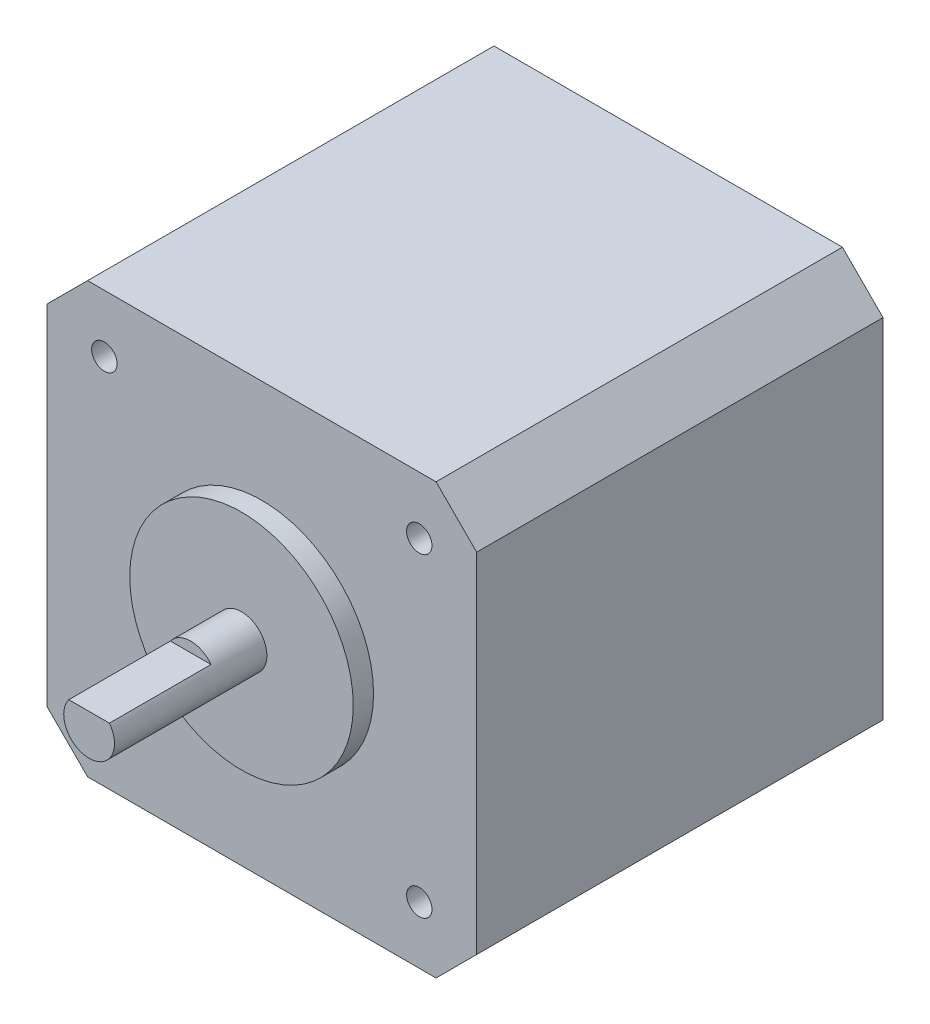
SolidWorks part; units mm, degrees
ref_plane "前视基准面" through (0, 0, 0) normal (0, 0, 1) x (1, 0, 0)
ref_plane "上视基准面" through (0, 0, 0) normal (0, 1, 0) x (1, 0, 0)
ref_plane "右视基准面" through (0, 0, 0) normal (1, 0, 0) x (0, 0, -1)
sketch "草图1" plane through (0, 0, 0) normal (0, 0, 1) x (1, 0, 0)
  line L1 (-21.15, 21.15) -> (21.15, 21.15)
  line L2 (-21.15, 21.15) -> (-21.15, -21.15)
  line L3 (-21.15, -21.15) -> (21.15, -21.15)
  line L4 (21.15, 21.15) -> (21.15, -21.15)
  line L5 (-21.15, 21.15) -> (21.15, -21.15) construction
  line L6 (-21.15, -21.15) -> (21.15, 21.15) construction
  point P0 (0, 0)
  dimension "D1" = 42.3
  dimension "D2" = 42.3
extrude "凸台-拉伸1" add sketch "草图1" along normal blind 40
sketch "草图2" plane through (0, 0, 40) normal (0, 0, 1) x (1, 0, 0)
  circle A0 centre (0, 0) radius 11
  dimension "D1" = 22
extrude "凸台-拉伸2" add sketch "草图2" along normal blind 2
sketch "草图3" plane through (0, 0, 42) normal (0, 0, 1) x (1, 0, 0)
  circle A0 centre (0, 0) radius 2.5
  dimension "D1" = 5
extrude "凸台-拉伸3" add sketch "草图3" along normal blind 15
sketch "草图4" plane through (0, 0, 0) normal (1, 0, 0) x (0, 0, -1)
  line L0 (-57, 2.5) -> (-57, -2.5) construction
  line L1 (-69.3139, 11.202) -> (-47, 11.202)
  line L2 (-69.3139, 11.202) -> (-69.3139, 1.5)
  line L3 (-69.3139, 1.5) -> (-47, 1.5)
  line L4 (-47, 11.202) -> (-47, 1.5)
  line L5 (-69.3139, 11.202) -> (-47, 1.5) construction
  line L6 (-69.3139, 1.5) -> (-47, 11.202) construction
  line L7 (-42, 2.5) -> (-57, 2.5) construction
  line L8 (-42, 2.5) -> (-57, 2.5)
  point P0 (-58.157, 6.351)
  dimension "D1" = 22.3139
  dimension "D2" = 10
  dimension "D3" = 1
extrude "切除-拉伸1" cut sketch "草图4" against normal mid plane 22 contours L1 L4 L3 L2
chamfer "倒角1" distance 4 angle 45 4 edges at (21.15, -21.15, 20) (-21.15, -21.15, 20) (-21.15, 21.15, 20) (21.15, 21.15, 20)
sketch "草图8" plane through (0, 0, 40) normal (0, 0, 1) x (1, 0, 0)
  line L1 (-15.5, 15.5) -> (15.5, 15.5)
  line L2 (-15.5, 15.5) -> (-15.5, -15.5)
  line L3 (-15.5, -15.5) -> (15.5, -15.5)
  line L4 (15.5, 15.5) -> (15.5, -15.5)
  line L5 (-15.5, 15.5) -> (15.5, -15.5) construction
  line L6 (-15.5, -15.5) -> (15.5, 15.5) construction
  point P0 (0, 0)
  dimension "D1" = 31
  dimension "D2" = 31
hole_wizard "M3 螺纹孔1" positions "草图10" profile "草图9" tap size "M3" standard "GB"
sketch "草图10" plane through (0, 0, 40) normal (0, 0, 1) x (1, 0, 0)
  point P0 (-15.5, 15.5)
  point P3 (-15.5, -15.5)
  point P6 (15.5, -15.5)
  point P9 (15.5, 15.5)
sketch "草图9" plane through (-15.5, 15.5, 40) normal (1, 0, 0) x (0, -1, 0)
  line L0 (0, 0) -> (0, 8.2511)
  line L1 (0, 8.2511) -> (1.25, 7.5)
  line L2 (1.25, 7.5) -> (1.25, 0)
  line L5 (1.25, 0) -> (0, 0)
  line L10 (0, 8.2511) -> (-1.25, 7.5) construction
  line L11 (0, -6.35) -> (0, 107.95) construction
  dimension "螺纹孔钻头直径" = 2.5
  dimension "螺纹孔钻头深度" = 7.5
  dimension "导头角度" = 118
cosmetic thread "孔螺蚊线1" parameters "D1"=6, "D2"=3
cosmetic thread "孔螺蚊线2" parameters "D1"=6, "D2"=3
cosmetic thread "孔螺蚊线3" parameters "D1"=6, "D2"=3
cosmetic thread "孔螺蚊线4" parameters "D1"=6, "D2"=3
